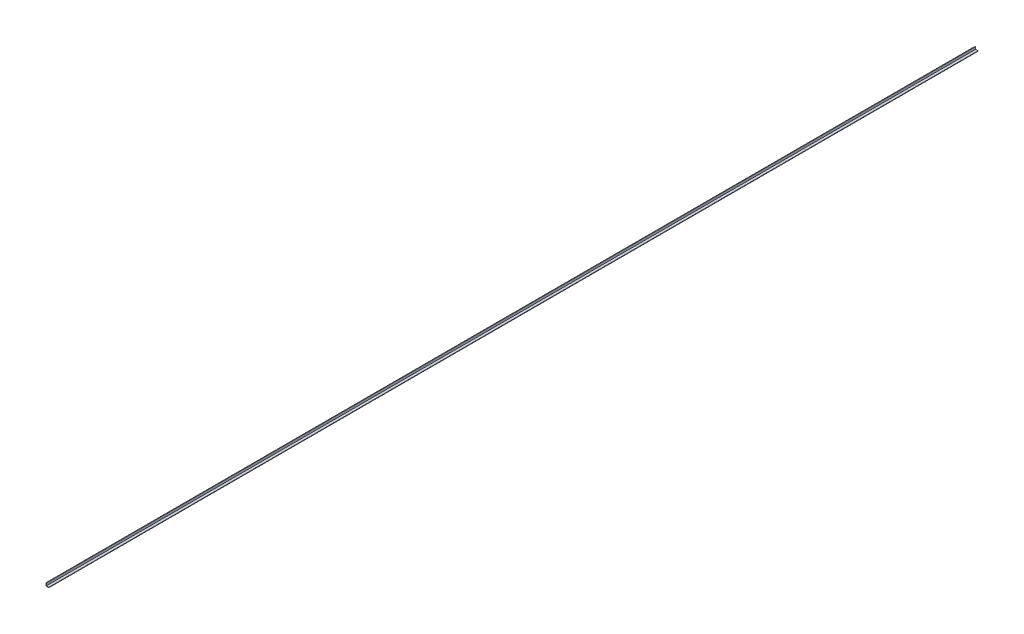
SolidWorks part; units mm, degrees
material "ASTM A36 Acero"
ref_plane "Alzado" through (0, 0, 0) normal (0, 0, 1) x (1, 0, 0)
ref_plane "Planta" through (0, 0, 0) normal (0, 1, 0) x (1, 0, 0)
ref_plane "Vista lateral" through (0, 0, 0) normal (1, 0, 0) x (0, 0, -1)
sketch "Croquis1" plane through (0, 0, 0) normal (0, 0, 1) x (1, 0, 0)
  line L0 (0, 19.05) -> (0, 0)
  line L1 (0, 0) -> (19.05, 0)
  line L2 (19.05, 0) -> (19.05, 3.18)
  line L3 (19.05, 3.18) -> (3.18, 3.18)
  line L4 (3.18, 3.18) -> (3.18, 19.05)
  line L5 (3.18, 19.05) -> (0, 19.05)
  dimension "D1" = 3.18
  dimension "D2" = 19.05
extrude "Saliente-Extruir1" add sketch "Croquis1" against normal blind 6100
